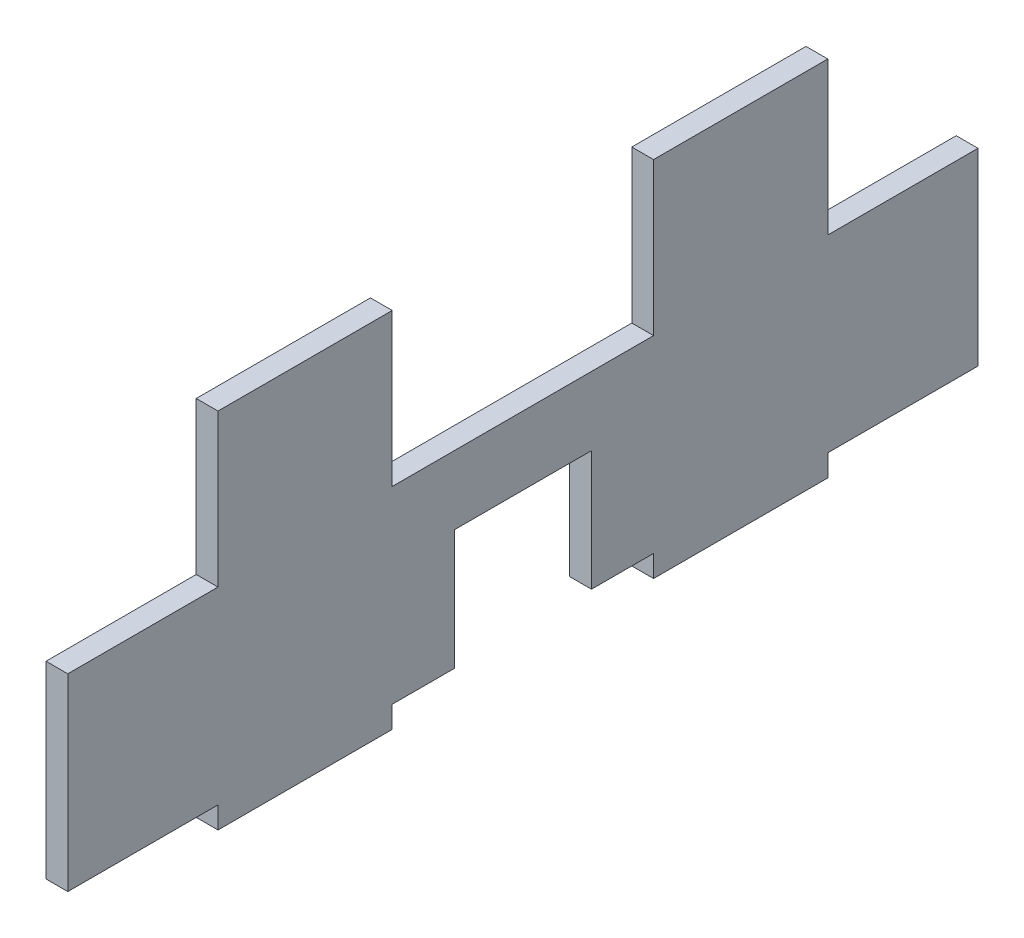
SolidWorks part; units mm, degrees
material "Acrylic (Medium-high impact)"
ref_plane "Front Plane" through (0, 0, 0) normal (0, 0, 1) x (1, 0, 0)
ref_plane "Top Plane" through (0, 0, 0) normal (0, 1, 0) x (1, 0, 0)
ref_plane "Right Plane" through (0, 0, 0) normal (1, 0, 0) x (0, 0, -1)
sketch "Sketch2" plane through (0, 0, 0) normal (0, 1, 0) x (1, 0, 0)
  line L0 (-147.5, 0) -> (147.5, 0) construction
  line L5 (-185, 195.2) -> (185, 195.2) construction
  line L6 (-197.7, -132.7) -> (197.7, -132.7)
  line L13 (110, 120) -> (185, 120)
  line L14 (110, 120) -> (110, -120)
  line L15 (110, -120) -> (185, -120)
  line L16 (185, 120) -> (185, -120)
  line L17 (110, 120) -> (185, -120) construction
  line L18 (110, -120) -> (185, 120) construction
  line L19 (-185, 120) -> (-110, 120)
  line L20 (-185, 120) -> (-185, -120)
  line L21 (-185, -120) -> (-110, -120)
  line L22 (-110, 120) -> (-110, -120)
  line L23 (-185, 120) -> (-110, -120) construction
  line L24 (-185, -120) -> (-110, 120) construction
  line L26 (-110, -37.5) -> (110, -37.5)
  line L27 (-110, -37.5) -> (-110, 37.5)
  line L28 (-110, 37.5) -> (110, 37.5)
  line L29 (110, -37.5) -> (110, 37.5)
  line L30 (-110, -37.5) -> (110, 37.5) construction
  line L31 (-110, 37.5) -> (110, -37.5) construction
  line L41 (-197.7, -132.7) -> (-197.7, 132.7)
  line L42 (-185, 132.7) -> (185, 132.7) construction
  line L43 (197.7, -132.7) -> (197.7, 132.7)
  line L44 (-197.7, -132.7) -> (197.7, 132.7) construction
  line L45 (-197.7, 132.7) -> (197.7, -132.7) construction
  line L47 (-197.7, 132.7) -> (-197.7, 257.7)
  line L48 (-197.7, 257.7) -> (-185, 257.7)
  line L49 (-185, 132.7) -> (-185, 257.7)
  line L51 (185, 132.7) -> (185, 257.7)
  line L52 (185, 257.7) -> (197.7, 257.7)
  line L53 (197.7, 132.7) -> (197.7, 257.7)
  line L54 (-185, 132.7) -> (185, 132.7)
  line L55 (223.1, 132.7) -> (223.1, 283.1)
  line L56 (159.6, 283.1) -> (223.1, 283.1)
  line L57 (159.6, 158.1) -> (159.6, 283.1)
  line L58 (-159.6, 158.1) -> (159.6, 158.1)
  line L59 (-159.6, 158.1) -> (-159.6, 283.1)
  line L60 (-223.1, 283.1) -> (-159.6, 283.1)
  line L61 (-223.1, 132.7) -> (-223.1, 283.1)
  line L62 (-223.1, -158.1) -> (-223.1, 132.7)
  line L63 (-223.1, -158.1) -> (223.1, -158.1)
  line L64 (223.1, -158.1) -> (223.1, 132.7)
  circle A0 centre (0, 308.1) radius 150
  point P2 (0, 0)
  point P13 (147.5, 0)
  point P18 (-147.5, 0)
  point P23 (0, 0)
  point P24 (0, 0)
  point P35 (0, 195.2)
  dimension "D1" = 300
  dimension "D2" = 75
  dimension "D3" = 240
  dimension "D4" = 75
  dimension "D5" = 220
  dimension "D6" = 12.7
  dimension "D7" = 12.7
  dimension "D8" = 12.7
  dimension "D9" = 125
  dimension "D10" = 25.4
sketch "Sketch3" plane through (0, 0, 0) normal (1, 0, 0) x (0, 0, -1)
  line L1 (-132.7, 0) -> (257.7, 0)
  line L2 (-132.7, 0) -> (-132.7, 55)
  line L3 (-132.7, 55) -> (257.7, 55)
  line L4 (257.7, 0) -> (257.7, 55)
  line L5 (-20, -35) -> (20, -35)
  line L6 (-20, -35) -> (-20, 35)
  line L7 (-20, 35) -> (20, 35)
  line L8 (20, -35) -> (20, 35)
  line L9 (-20, -35) -> (20, 35) construction
  line L10 (-20, 35) -> (20, -35) construction
  point P7 (0, 0)
  dimension "D1" = 55
  dimension "D2" = 40
  dimension "D3" = 70
extrude "Boss-Extrude1" add sketch "Sketch3" along normal blind 6.35 contours L8 L1 L4 L3 L2 L6 L7
sketch "Sketch4" plane through (0, 0, 0) normal (0, -1, 0) x (1, 0, 0)
  line L0 (0, -20) -> (0, -257.7) construction
  line L1 (0, -257.7) -> (6.35, -257.7) construction
  line L2 (6.35, -257.7) -> (6.35, -20) construction
  line L3 (6.35, -20) -> (0, -20) construction
  line L4 (0, 132.7) -> (0, 20) construction
  line L5 (0, 20) -> (6.35, 20) construction
  line L6 (6.35, 20) -> (6.35, 132.7) construction
  line L7 (6.35, 132.7) -> (0, 132.7) construction
  line L8 (0, -20) -> (0, -257.7)
  line L9 (0, -257.7) -> (6.35, -257.7)
  line L10 (6.35, -257.7) -> (6.35, -20)
  line L11 (6.35, -20) -> (0, -20)
  line L12 (0, 132.7) -> (0, 20)
  line L13 (0, 20) -> (6.35, 20)
  line L14 (6.35, 20) -> (6.35, 132.7)
  line L15 (6.35, 132.7) -> (0, 132.7)
extrude "Boss-Extrude2" add sketch "Sketch4" along normal blind 6.35
sketch "Sketch5" plane through (0, 55, 0) normal (0, 1, 0) x (1, 0, 0)
  line L4 (0, 257.7) -> (0, -132.7)
  line L5 (0, -132.7) -> (6.35, -132.7)
  line L6 (6.35, -132.7) -> (6.35, 257.7)
  line L7 (6.35, 257.7) -> (0, 257.7)
  line L8 (0, 257.7) -> (0, -132.7)
  line L9 (0, -132.7) -> (6.35, -132.7)
  line L10 (6.35, -132.7) -> (6.35, 257.7)
  line L11 (6.35, 257.7) -> (0, 257.7)
  dimension "D1" = 0
extrude "Boss-Extrude3" add sketch "Sketch5" along normal blind 6.35
sketch "Sketch6" plane through (6.35, 0, 0) normal (1, 0, 0) x (0, 0, -1)
  line L0 (257.7, -6.35) -> (20, -6.35) construction
  line L1 (257.7, 61.35) -> (132.7, 61.35)
  line L2 (257.7, 61.35) -> (257.7, -6.35)
  line L3 (257.7, -6.35) -> (132.7, -6.35)
  line L4 (132.7, 61.35) -> (132.7, -6.35)
  line L5 (20, 35) -> (132.7, 35) construction
  line L6 (-20, -6.35) -> (-132.7, -6.35) construction
extrude "Cut-Extrude1" cut sketch "Sketch6" against normal through all
sketch "Sketch7" plane through (6.35, 0, 0) normal (1, 0, 0) x (0, 0, -1)
  line L0 (-126.35, 55) -> (-126.35, 0)
  line L1 (-126.35, 0) -> (-26.35, 0)
  line L2 (-26.35, 0) -> (-26.35, 41.35)
  line L3 (-26.35, 41.35) -> (26.35, 41.35)
  line L4 (26.35, 41.35) -> (26.35, 0)
  line L5 (26.35, 0) -> (126.35, 0)
  line L6 (126.35, 0) -> (126.35, 55)
  line L7 (126.35, 55) -> (-126.35, 55)
  line L8 (132.7, -6.35) -> (132.7, 61.35)
  line L9 (132.7, 61.35) -> (-132.7, 61.35)
  line L10 (-132.7, 61.35) -> (-132.7, -6.35)
  line L11 (-132.7, -6.35) -> (-20, -6.35)
  line L12 (-20, -6.35) -> (-20, 35)
  line L13 (-20, 35) -> (20, 35)
  line L14 (20, 35) -> (20, -6.35)
  line L15 (20, -6.35) -> (132.7, -6.35)
  line L16 (132.7, -6.35) -> (132.7, 61.35)
  line L17 (132.7, 61.35) -> (-132.7, 61.35)
  line L18 (-132.7, 61.35) -> (-132.7, -6.35)
  line L19 (-132.7, -6.35) -> (-20, -6.35)
  line L20 (-20, -6.35) -> (-20, 35)
  line L21 (-20, 35) -> (20, 35)
  line L22 (20, 35) -> (20, -6.35)
  line L23 (20, -6.35) -> (132.7, -6.35)
  line L24 (-26.35, 0) -> (26.35, 0)
  line L25 (-126.35, 0) -> (-132.7, 0)
  line L26 (-88.9, 0) -> (-38.1, 0)
  line L27 (-88.9, 0) -> (-88.9, -6.35)
  line L28 (-88.9, -6.35) -> (-38.1, -6.35)
  line L29 (-38.1, 0) -> (-38.1, -6.35)
  line L30 (38.1, 0) -> (88.9, 0)
  line L31 (38.1, 0) -> (38.1, -6.35)
  line L32 (38.1, -6.35) -> (88.9, -6.35)
  line L33 (88.9, 0) -> (88.9, -6.35)
  line L34 (-132.7, 0) -> (132.7, 0)
  line L35 (-132.7, 27.5) -> (132.7, 27.5) construction
  line L36 (38.1, 61.35) -> (88.9, 61.35)
  line L37 (88.9, 55) -> (88.9, 61.35)
  line L38 (38.1, 55) -> (88.9, 55)
  line L39 (38.1, 55) -> (38.1, 61.35)
  line L40 (-88.9, 61.35) -> (-38.1, 61.35)
  line L41 (-38.1, 55) -> (-38.1, 61.35)
  line L42 (-88.9, 55) -> (-38.1, 55)
  line L43 (-88.9, 55) -> (-88.9, 61.35)
  line L44 (-132.7, 55) -> (132.7, 55)
  point P24 (0, 0)
  line M13 (132.7, -6.35) -> (132.7, 61.35)
  line M14 (132.7, 61.35) -> (-132.7, 61.35)
  line M15 (-132.7, 61.35) -> (-132.7, -6.35)
  line M16 (-132.7, -6.35) -> (-20, -6.35)
  line M17 (-20, -6.35) -> (-20, 35)
  line M20 (20, -6.35) -> (132.7, -6.35)
  dimension "D3" = 38.1
  dimension "D4" = 38.1
  dimension "D5" = 50.8
  dimension "D6" = 50.8
  dimension "D1" = 0
  dimension "D2" = 6.35
extrude "Cut-Extrude2" cut sketch "Sketch7" against normal through all contours L27 L1 L25 L18 M16 | L1 L29 L24 M16 M17 | L31 L5 L24 L22 M20 | L34 L5 L33 M20 M13 | L7 L44 L37 M13 M14 | L41 L7 L39 M14 | L44 L7 L43 M15 M14
sketch "Sketch8" plane through (0, 61.35, 0) normal (0, 1, 0) x (1, 0, 0)
  line L0 (6.35, 38.1) -> (6.35, 88.9) construction
  line L1 (6.35, 88.9) -> (0, 88.9) construction
  line L2 (0, 88.9) -> (0, 38.1) construction
  line L3 (0, 38.1) -> (6.35, 38.1) construction
  line L4 (6.35, -88.9) -> (6.35, -38.1) construction
  line L5 (6.35, -38.1) -> (0, -38.1) construction
  line L6 (0, -38.1) -> (0, -88.9) construction
  line L7 (0, -88.9) -> (6.35, -88.9) construction
  line L8 (6.35, 38.1) -> (6.35, 88.9)
  line L9 (6.35, 88.9) -> (0, 88.9)
  line L10 (0, 88.9) -> (0, 38.1)
  line L11 (0, 38.1) -> (6.35, 38.1)
  line L12 (6.35, -88.9) -> (6.35, -38.1)
  line L13 (6.35, -38.1) -> (0, -38.1)
  line L14 (0, -38.1) -> (0, -88.9)
  line L15 (0, -88.9) -> (6.35, -88.9)
extrude "Boss-Extrude4" add sketch "Sketch8" along normal blind 38.1
